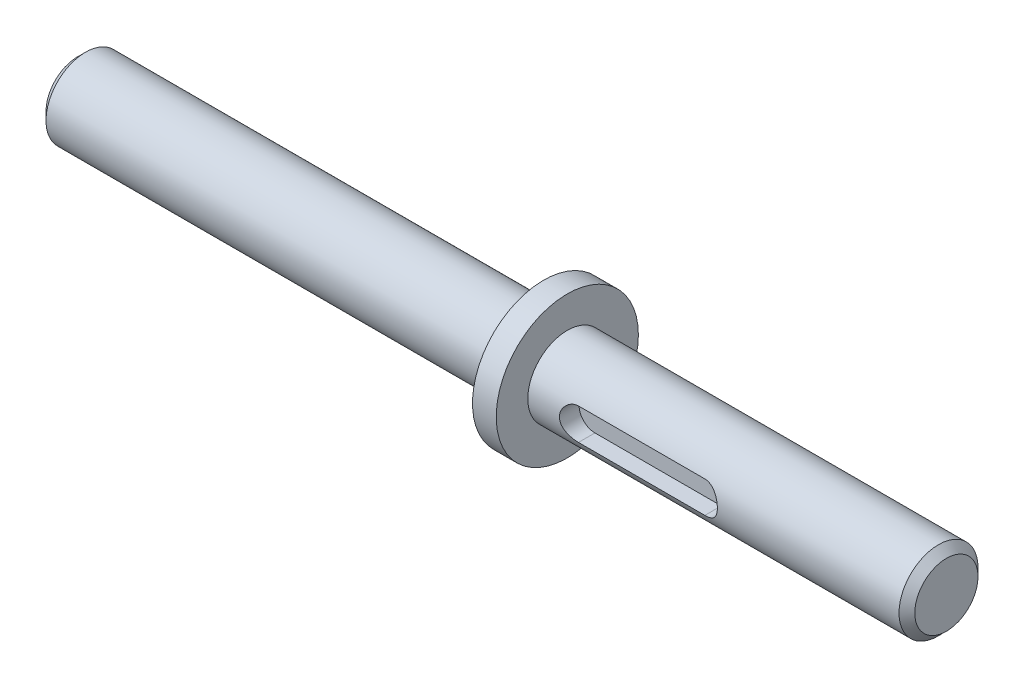
SolidWorks part; units mm, degrees
ref_plane "Front" through (0, 0, 0) normal (0, 0, 1) x (1, 0, 0)
ref_plane "Top" through (0, 0, 0) normal (0, 1, 0) x (1, 0, 0)
ref_plane "Right" through (0, 0, 0) normal (1, 0, 0) x (0, 0, -1)
sketch "Sketch1" plane through (0, 0, 0) normal (0, 1, 0) x (1, 0, 0)
  line L0 (-59, 0) -> (-59, -5)
  line L1 (-59, -5) -> (0, -5)
  line L2 (0, -5) -> (0, -9)
  line L3 (0, -9) -> (3, -9)
  line L4 (3, -9) -> (3, -5)
  line L5 (3, -5) -> (51, -5)
  line L6 (51, -5) -> (51, 0)
  line L7 (51, 0) -> (-59, 0)
  line L8 (0, 0) -> (-68.296, 0) construction
  dimension "D1" = 10
  dimension "D2" = 18
  dimension "D3" = 48
  dimension "D4" = 3
  dimension "D5" = 59
revolve "Revolve1" add sketch "Sketch1" angle 360 about L8
ref_plane "Plane1" through (0, 0, 5) normal (0, 0, 1) x (1, 0, 0)
sketch "Sketch2" plane through (0, 0, 5) normal (0, 0, 1) x (1, 0, 0)
  line L0 (9, 2) -> (25, 2)
  line L1 (9, -2) -> (25, -2)
  line L2 (0, 9) -> (0, -9) construction
  arc A0 (9, 2) -> (9, -2) centre (9, 0) ccw
  arc A1 (25, -2) -> (25, 2) centre (25, 0) ccw
  dimension "D1" = 16
  dimension "D2" = 2
  dimension "D3" = 9
extrude "Cut-Extrude1" cut sketch "Sketch2" against normal blind 2.5
chamfer "Chamfer1" distance 1 angle 45 2 edges at (-59, 0, -5) (51, 0, -5)
